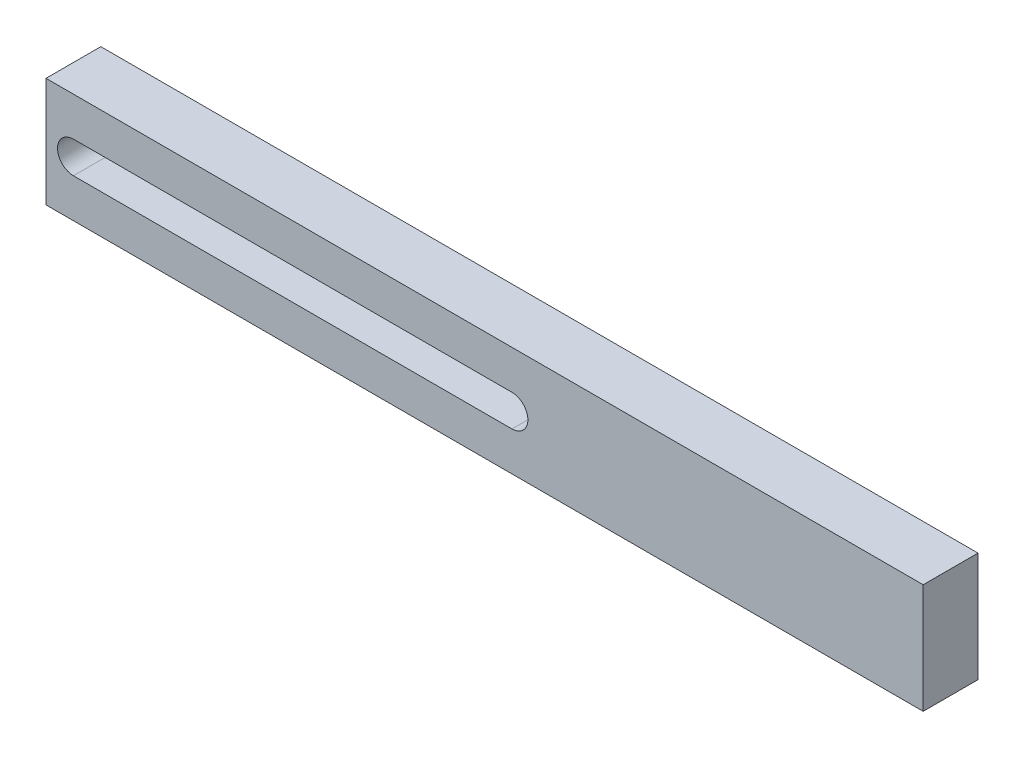
SolidWorks part; units mm, degrees
ref_plane "Front Plane" through (0, 0, 0) normal (0, 0, 1) x (1, 0, 0)
ref_plane "Top Plane" through (0, 0, 0) normal (0, 1, 0) x (1, 0, 0)
ref_plane "Right Plane" through (0, 0, 0) normal (1, 0, 0) x (0, 0, -1)
sketch "Sketch1" plane through (0, 0, 0) normal (0, 0, 1) x (1, 0, 0)
  line L1 (-101.6, -12.7) -> (101.6, -12.7)
  line L2 (-101.6, -12.7) -> (-101.6, 12.7)
  line L3 (-101.6, 12.7) -> (101.6, 12.7)
  line L4 (101.6, -12.7) -> (101.6, 12.7)
  line L5 (-101.6, -12.7) -> (101.6, 12.7) construction
  line L6 (-101.6, 12.7) -> (101.6, -12.7) construction
  point P0 (0, 0)
  dimension "D1" = 203.2
  dimension "D2" = 25.4
extrude "Boss-Extrude1" add sketch "Sketch1" along normal mid plane 12.7
sketch "Sketch2" plane through (0, 0, 6.35) normal (0, 0, 1) x (1, 0, 0)
  line L0 (-95.25, 0) -> (6.35, 0) construction
  line L1 (-95.25, 3.675) -> (6.35, 3.675)
  line L2 (-95.25, -3.675) -> (6.35, -3.675)
  line L3 (-101.6, 12.7) -> (-101.6, -12.7) construction
  arc A0 (-95.25, 3.675) -> (-95.25, -3.675) centre (-95.25, 0) ccw
  arc A1 (6.35, -3.675) -> (6.35, 3.675) centre (6.35, 0) ccw
  point P3 (-44.45, 0)
  point P8 (0, 0)
  dimension "D1" = 7.35
  dimension "D2" = 6.35
  dimension "D3" = 101.6
extrude "Cut-Extrude1" cut sketch "Sketch2" against normal through all both and the other way through all
